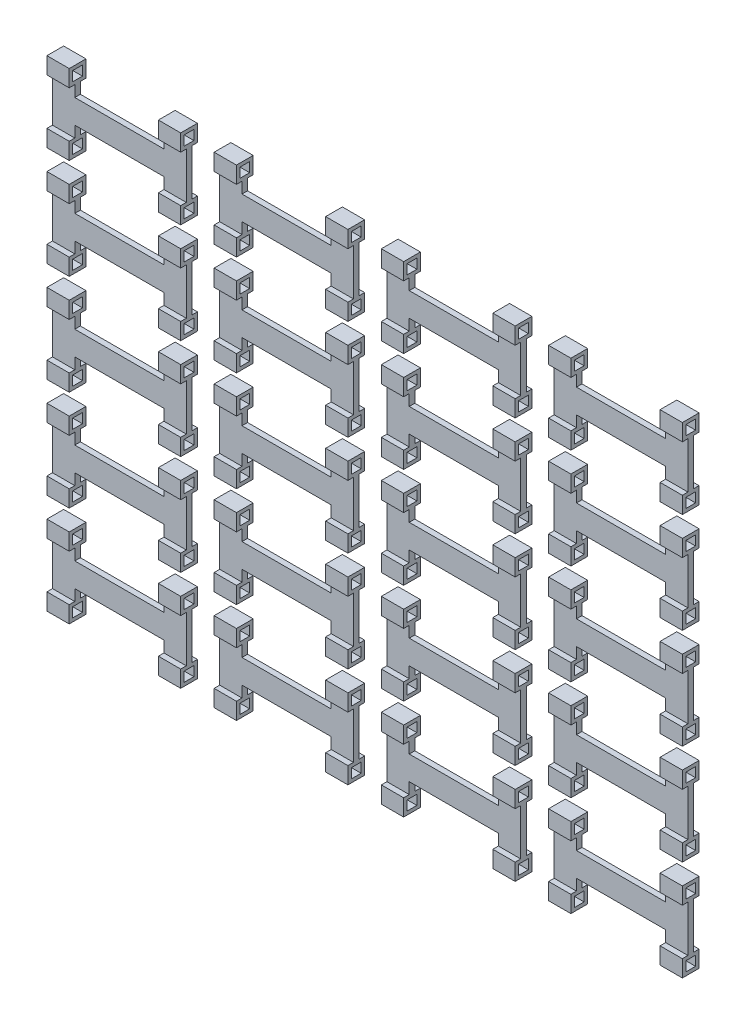
SolidWorks part; units mm, degrees
ref_plane "前视基准面" through (0, 0, 0) normal (0, 0, 1) x (1, 0, 0)
ref_plane "上视基准面" through (0, 0, 0) normal (0, 1, 0) x (1, 0, 0)
ref_plane "右视基准面" through (0, 0, 0) normal (1, 0, 0) x (0, 0, -1)
sketch "草图1" plane through (0, 0, 0) normal (1, 0, 0) x (0, 0, -1)
  line L0 (0, 0) -> (0, 11.3) construction
  line L1 (-0.87, -0.87) -> (0.87, -0.87)
  line L2 (-0.87, -0.87) -> (-0.87, 0.87)
  line L3 (-0.87, 0.87) -> (0.87, 0.87)
  line L4 (0.87, -0.87) -> (0.87, 0.87)
  line L5 (-0.87, -0.87) -> (0.87, 0.87) construction
  line L6 (-0.87, 0.87) -> (0.87, -0.87) construction
  line L7 (-0.87, 10.43) -> (0.87, 10.43)
  line L8 (-0.87, 10.43) -> (-0.87, 12.17)
  line L9 (-0.87, 12.17) -> (0.87, 12.17)
  line L10 (0.87, 10.43) -> (0.87, 12.17)
  line L11 (-0.87, 10.43) -> (0.87, 12.17) construction
  line L12 (-0.87, 12.17) -> (0.87, 10.43) construction
  line L13 (0.5, 9.8) -> (1.5, 9.8)
  line L14 (-1.5, 12.8) -> (1.5, 12.8)
  line L15 (-1.5, 12.8) -> (-1.5, 9.8)
  line L16 (-1.5, 9.8) -> (-0.5, 9.8)
  line L17 (1.5, 12.8) -> (1.5, 9.8)
  line L18 (-1.5, 12.8) -> (1.5, 9.8) construction
  line L19 (-1.5, 9.8) -> (1.5, 12.8) construction
  line L20 (-1.5, 1.5) -> (1.5, 1.5)
  line L21 (-1.5, 1.5) -> (-1.5, -1.5)
  line L22 (-1.5, -1.5) -> (1.5, -1.5)
  line L23 (1.5, 1.5) -> (1.5, -1.5)
  line L24 (-1.5, 1.5) -> (1.5, -1.5) construction
  line L25 (-1.5, -1.5) -> (1.5, 1.5) construction
  line L26 (-0.5, 1.5) -> (0.5, 1.5)
  line L27 (-0.5, 1.5) -> (-0.5, 9.8)
  line L29 (0.5, 1.5) -> (0.5, 9.8)
  line L30 (-0.5, 1.5) -> (0.5, 9.8) construction
  line L31 (-0.5, 9.8) -> (0.5, 1.5) construction
  point P0 (0, 0)
  point P6 (0, 11.3)
  point P21 (0, 5.65)
  dimension "D1" = 11.3
  dimension "D2" = 1.74
  dimension "D3" = 3
  dimension "D4" = 1
extrude "凸台-拉伸1" add sketch "草图1" along normal blind 24 contours L20 L29 L13 L17 L14 L15 L16 L27 L10 L7 L8 L9 | L23 L20 L21 L22 L4 L1 L2 L3
sketch "草图2" plane through (0, 0, 0) normal (0, 0, 1) x (1, 0, 0)
  line L0 (24, 12.8) -> (0, 12.8) construction
  line L1 (4, 17.8) -> (20, 17.8)
  line L2 (4, 17.8) -> (4, 7.8)
  line L3 (4, 7.8) -> (20, 7.8)
  line L4 (20, 17.8) -> (20, 7.8)
  line L5 (4, 17.8) -> (20, 7.8) construction
  line L6 (4, 7.8) -> (20, 17.8) construction
  line L7 (24, -1.5) -> (0, -1.5) construction
  line L8 (4, -6.5) -> (20, -6.5)
  line L9 (4, -6.5) -> (4, 3.5)
  line L10 (4, 3.5) -> (20, 3.5)
  line L11 (20, -6.5) -> (20, 3.5)
  line L12 (4, -6.5) -> (20, 3.5) construction
  line L13 (4, 3.5) -> (20, -6.5) construction
  point P0 (12, 12.8)
  point P7 (12, -1.5)
  dimension "D1" = 16
  dimension "D2" = 10
extrude "切除-拉伸1" cut sketch "草图2" against normal through all both and the other way through all
pattern_linear "阵列(线性)1" count 5 spacing 18 along (0, -1, 0) count 4 spacing 30 along (-1, 0, 0) of bodies 107
